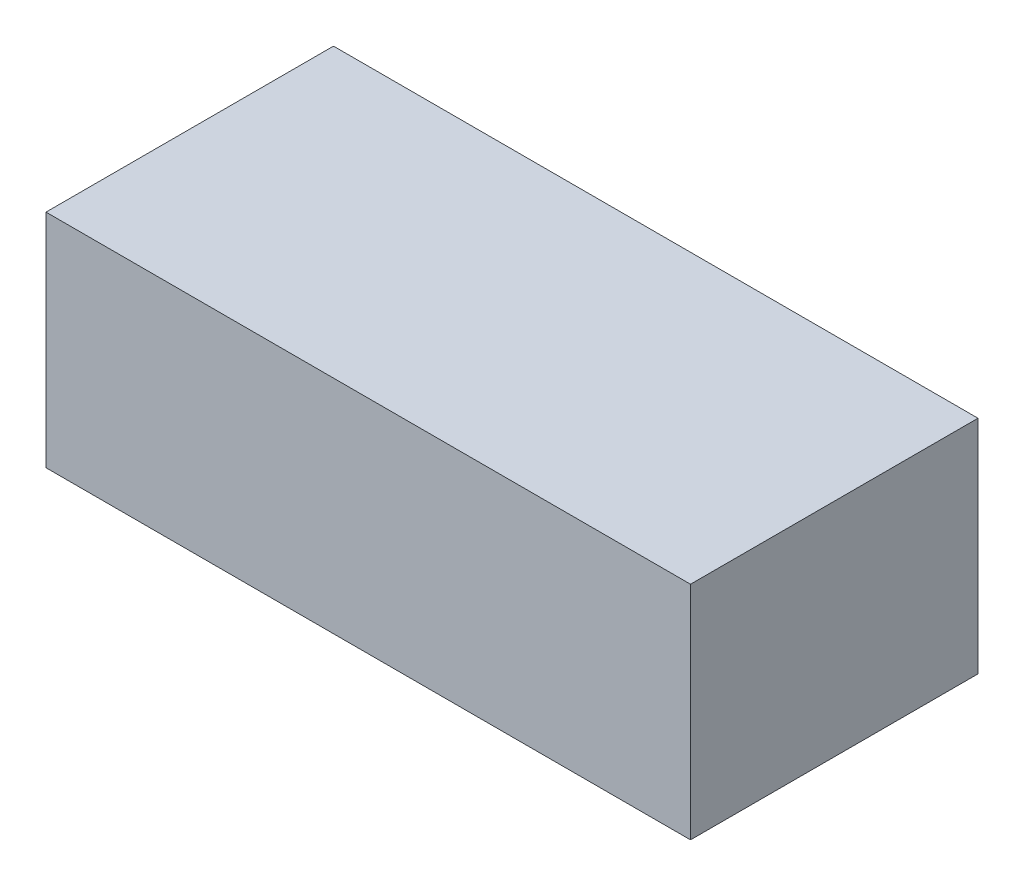
SolidWorks part; units mm, degrees
ref_plane "Front Plane" through (0, 0, 0) normal (0, 0, 1) x (1, 0, 0)
ref_plane "Top Plane" through (0, 0, 0) normal (0, 1, 0) x (1, 0, 0)
ref_plane "Right Plane" through (0, 0, 0) normal (1, 0, 0) x (0, 0, -1)
sketch "Sketch1" plane through (0, 0, 0) normal (1, 0, 0) x (0, 0, -1)
  line L1 (-16.75, -12.9) -> (16.75, -12.9)
  line L2 (-16.75, -12.9) -> (-16.75, 12.9)
  line L3 (-16.75, 12.9) -> (16.75, 12.9)
  line L4 (16.75, -12.9) -> (16.75, 12.9)
  line L5 (-16.75, -12.9) -> (16.75, 12.9) construction
  line L6 (-16.75, 12.9) -> (16.75, -12.9) construction
  point P0 (0, 0)
  dimension "D1" = 25.8
  dimension "D2" = 33.5
extrude "Boss-Extrude1" add sketch "Sketch1" along normal blind 75.1
